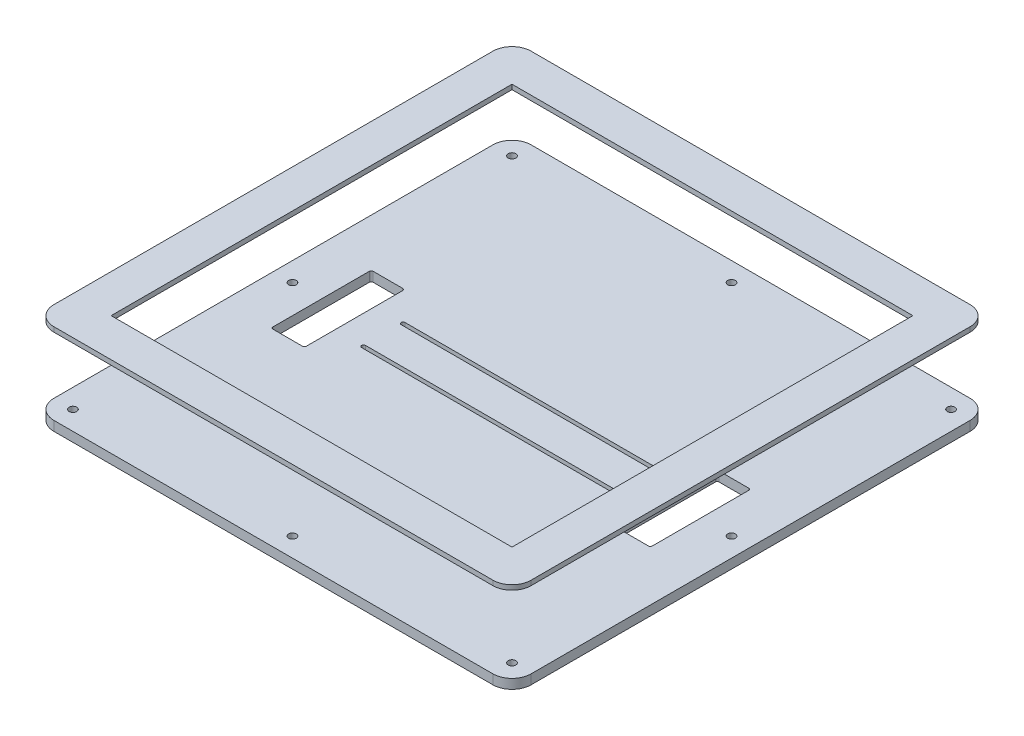
SolidWorks part; units mm, degrees
ref_plane "Front Plane" through (0, 0, 0) normal (0, 0, 1) x (1, 0, 0)
ref_plane "Top Plane" through (0, 0, 0) normal (0, 1, 0) x (1, 0, 0)
ref_plane "Right Plane" through (0, 0, 0) normal (1, 0, 0) x (0, 0, -1)
sketch "Sketch1" plane through (0, 0, 0) normal (0, 1, 0) x (1, 0, 0)
  line L1 (-230, -250) -> (230, -250)
  line L2 (-250, -230) -> (-250, 230)
  line L3 (-230, 250) -> (230, 250)
  line L4 (250, -230) -> (250, 230)
  line L5 (-250, -250) -> (250, 250) construction
  line L6 (-250, 250) -> (250, -250) construction
  line L7 (0, 250) -> (0, -250) construction
  line L8 (-250, 0) -> (250, 0) construction
  line L9 (-198, -52.5) -> (-167, -52.5)
  line L10 (-200, -50.5) -> (-200, 50.5)
  line L11 (-198, 52.5) -> (-167, 52.5)
  line L12 (-165, -50.5) -> (-165, 50.5)
  line L13 (-200, -52.5) -> (-165, 52.5) construction
  line L14 (-200, 52.5) -> (-165, -52.5) construction
  line L15 (195.5, -52.5) -> (164.5, -52.5)
  line L16 (197.5, -50.5) -> (197.5, 50.5)
  line L17 (195.5, 52.5) -> (164.5, 52.5)
  line L18 (162.5, -50.5) -> (162.5, 50.5)
  line L19 (197.5, -52.5) -> (162.5, 52.5) construction
  line L20 (197.5, 52.5) -> (162.5, -52.5) construction
  arc A0 (230, 250) -> (250, 230) centre (230, 230) cw
  arc A1 (250, -230) -> (230, -250) centre (230, -230) cw
  arc A2 (-230, -250) -> (-250, -230) centre (-230, -230) cw
  arc A3 (-250, 230) -> (-230, 250) centre (-230, 230) cw
  circle A4 centre (-230, 230) radius 4
  circle A5 centre (230, 230) radius 4
  circle A6 centre (230, -230) radius 4
  circle A7 centre (-230, -230) radius 4
  arc A10 (162.5, -50.5) -> (164.5, -52.5) centre (164.5, -50.5) ccw
  arc A11 (195.5, -52.5) -> (197.5, -50.5) centre (195.5, -50.5) ccw
  arc A12 (197.5, 50.5) -> (195.5, 52.5) centre (195.5, 50.5) ccw
  arc A13 (162.5, 50.5) -> (164.5, 52.5) centre (164.5, 50.5) cw
  arc A14 (-167, 52.5) -> (-165, 50.5) centre (-167, 50.5) cw
  arc A15 (-165, -50.5) -> (-167, -52.5) centre (-167, -50.5) cw
  arc A16 (-198, -52.5) -> (-200, -50.5) centre (-198, -50.5) cw
  arc A17 (-200, 50.5) -> (-198, 52.5) centre (-198, 50.5) cw
  circle A18 centre (0, 230) radius 4
  circle A19 centre (-230, 0) radius 4
  circle A20 centre (230, 0) radius 4
  circle A21 centre (0, -230) radius 4
  point P0 (0, 0)
  point P26 (180, 0)
  point P35 (-182.5, 0)
  dimension "D3" = 20
  dimension "D4" = 8
  dimension "D5" = 50
  dimension "D10" = 2
  dimension "D11" = 2
  dimension "D1" = 500
  dimension "D2" = 500
  dimension "D6" = 35
sketch "Sketch2" plane through (0, 0, 0) normal (0, 0, 1) x (1, 0, 0)
  line L0 (0, 0) -> (0, 80) construction
  dimension "D1" = 80
ref_plane "Plane1" through (0, 80, 0) normal (0, 1, 0) x (1, 0, 0)
sketch "Sketch3" plane through (0, 80, 0) normal (0, 1, 0) x (1, 0, 0)
  line L1 (-230, -250) -> (230, -250)
  line L2 (-250, -230) -> (-250, 230)
  line L3 (-230, 250) -> (230, 250)
  line L4 (250, -230) -> (250, 230)
  line L5 (-250, -250) -> (-210, -210) construction
  line L6 (-250, 250) -> (-210, 210) construction
  line L17 (0, -210) -> (0, -250) construction
  line L18 (210, -210) -> (-210, -210)
  line L19 (0, 250) -> (0, 210) construction
  line L24 (210, -210) -> (210, 210)
  line L25 (210, 210) -> (-210, 210)
  line L26 (210, 210) -> (250, 250) construction
  line L33 (210, -210) -> (250, -250) construction
  line L35 (-210, -210) -> (-210, 210)
  line L36 (210, -210) -> (-210, 210) construction
  line L37 (210, 210) -> (-210, -210) construction
  arc A0 (230, 250) -> (250, 230) centre (230, 230) cw
  arc A1 (250, -230) -> (230, -250) centre (230, -230) cw
  arc A2 (-230, -250) -> (-250, -230) centre (-230, -230) cw
  arc A3 (-250, 230) -> (-230, 250) centre (-230, 230) cw
  point P0 (0, 0)
  point P19 (0, 0)
  point P20 (0, 0)
  point P21 (0, 0)
  point P22 (0, 0)
  point P23 (0, 0)
  point P24 (0, 230)
  point P27 (230, 0)
  point P32 (0, 0)
  point P33 (-230, 0)
  point P35 (0, -230)
  point P39 (0, 0)
  dimension "D1" = 20
extrude "Boss-Extrude1" add sketch "Sketch1" against normal blind 10
extrude "Boss-Extrude2" add sketch "Sketch3" along normal blind 5 separate body
sketch "Sketch8" plane through (0, 85, 0) normal (0, 1, 0) x (1, 0, 0)
  circle A0 centre (-230, 230) radius 4.2
  circle A1 centre (0, 230) radius 4.2
  circle A2 centre (230, 230) radius 4.2
  circle A4 centre (-230, 0) radius 4.2
  circle A7 centre (230, 0) radius 4.2
  circle A9 centre (230, -230) radius 4.2
  circle A10 centre (0, -230) radius 4.2
  circle A11 centre (-230, -230) radius 4.2
  dimension "D1" = 8.4
sketch "Sketch9" plane through (0, 0, 0) normal (0, 1, 0) x (1, 0, 0)
  line L0 (-250, -250) -> (250, 250) construction
  line L1 (-189.341, -89.341) -> (-89.341, -89.341)
  line L2 (-189.341, -89.341) -> (-189.341, -189.341)
  line L3 (-189.341, -189.341) -> (-89.341, -189.341)
  line L4 (-89.341, -89.341) -> (-89.341, -189.341)
  line L5 (-189.341, -89.341) -> (-89.341, -189.341) construction
  line L6 (-189.341, -189.341) -> (-89.341, -89.341) construction
  point P0 (-139.341, -139.341)
  dimension "D1" = 100
sketch "Sketch10" plane through (0, 0, 0) normal (0, 1, 0) x (1, 0, 0)
  line L4 (-52.25, 0) -> (52.25, 0) construction
  line L5 (0, -52.25) -> (0, 52.25) construction
  line L6 (0, 0) -> (67.0062, 0) construction
  line L7 (-134.8425, 22.75) -> (134.8425, 22.75)
  line L8 (134.8425, 18.75) -> (-134.8425, 18.75)
  line L9 (-134.8425, -18.75) -> (134.8425, -18.75)
  line L10 (134.8425, -22.75) -> (-134.8425, -22.75)
  arc A0 (-134.8425, 22.75) -> (-134.8425, 18.75) centre (-134.8425, 20.75) ccw
  arc A2 (-134.8425, -22.75) -> (-134.8425, -18.75) centre (-134.8425, -20.75) cw
  arc A3 (134.8425, -22.75) -> (134.8425, -18.75) centre (134.8425, -20.75) ccw
  arc A4 (134.8425, 22.75) -> (134.8425, 18.75) centre (134.8425, 20.75) cw
  dimension "D3" = 4
  dimension "D1" = 20.75
extrude "Cut-Extrude1" cut sketch "Sketch10" against normal up to next (10 mm away)
